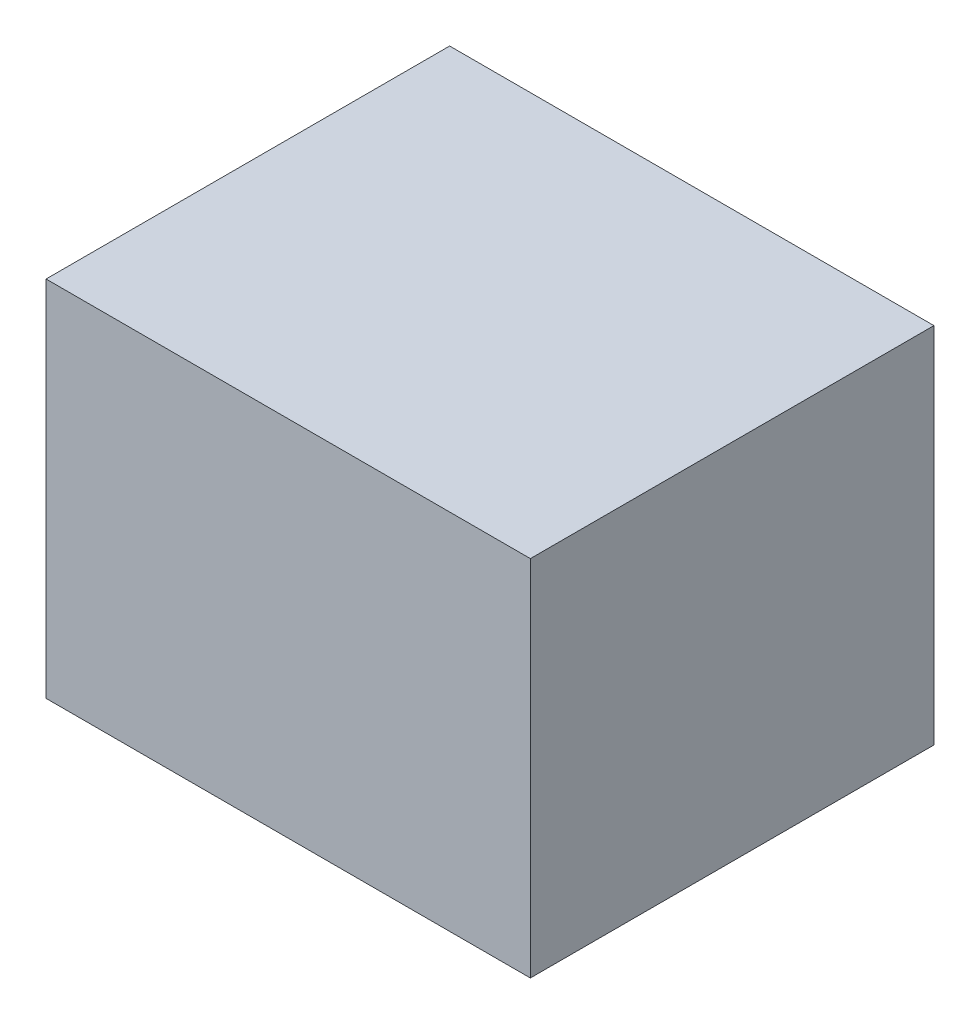
SolidWorks part; units mm, degrees
ref_plane "Front Plane" through (0, 0, 0) normal (0, 0, 1) x (1, 0, 0)
ref_plane "Top Plane" through (0, 0, 0) normal (0, 1, 0) x (1, 0, 0)
ref_plane "Right Plane" through (0, 0, 0) normal (1, 0, 0) x (0, 0, -1)
sketch "Sketch1" plane through (0, 0, 0) normal (0, 1, 0) x (1, 0, 0)
  line L1 (-152.4, -127) -> (152.4, -127)
  line L2 (-152.4, -127) -> (-152.4, 127)
  line L3 (-152.4, 127) -> (152.4, 127)
  line L4 (152.4, -127) -> (152.4, 127)
  line L5 (-152.4, -127) -> (152.4, 127) construction
  line L6 (-152.4, 127) -> (152.4, -127) construction
  point P0 (0, 0)
  dimension "D1" = 304.8
  dimension "D2" = 254
extrude "Boss-Extrude1" add sketch "Sketch1" along normal blind 228.6 contours L1 L4 L3 L2
